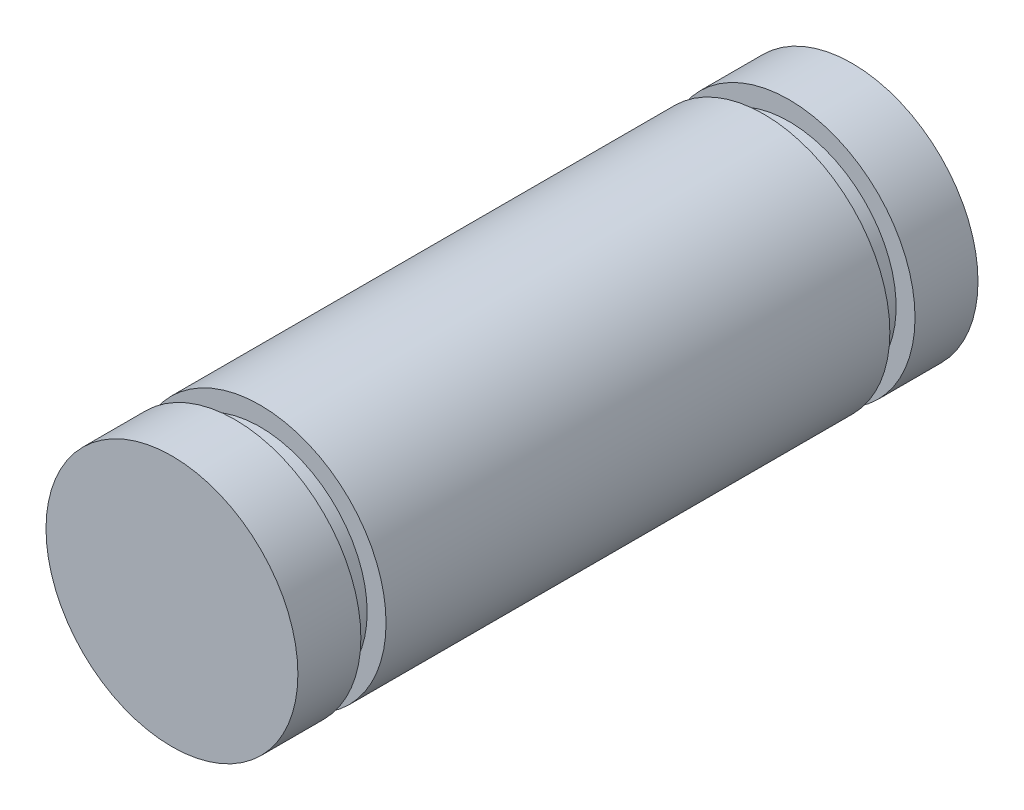
SolidWorks part; units mm, degrees
material "AISI 4130 Steel, normalized at 870C"
ref_plane "Front Plane" through (0, 0, 0) normal (0, 0, 1) x (1, 0, 0)
ref_plane "Top Plane" through (0, 0, 0) normal (0, 1, 0) x (1, 0, 0)
ref_plane "Right Plane" through (0, 0, 0) normal (1, 0, 0) x (0, 0, -1)
sketch "Sketch1" plane through (0, 0, 0) normal (0, 0, 1) x (1, 0, 0)
  circle A0 centre (0, 0) radius 10
extrude "Boss-Extrude1" add sketch "Sketch1" along normal blind 40
sketch "Sketch2" plane through (0, 0, 40) normal (0, 0, 1) x (1, 0, 0)
  circle A0 centre (0, 0) radius 8.5
extrude "Boss-Extrude2" add sketch "Sketch2" along normal blind 2
sketch "Sketch4" plane through (0, 0, 42) normal (0, 0, 1) x (1, 0, 0)
  circle A0 centre (0, 0) radius 10
extrude "Boss-Extrude3" add sketch "Sketch4" along normal blind 5
sketch "Sketch5" plane through (0, 0, 0) normal (0, 0, -1) x (-1, 0, 0)
  circle A0 centre (0, 0) radius 8.5
extrude "Boss-Extrude4" add sketch "Sketch5" along normal blind 2
sketch "Sketch6" plane through (0, 0, -2) normal (0, 0, -1) x (-1, 0, 0)
  circle A0 centre (0, 0) radius 10
extrude "Boss-Extrude5" add sketch "Sketch6" along normal blind 5
